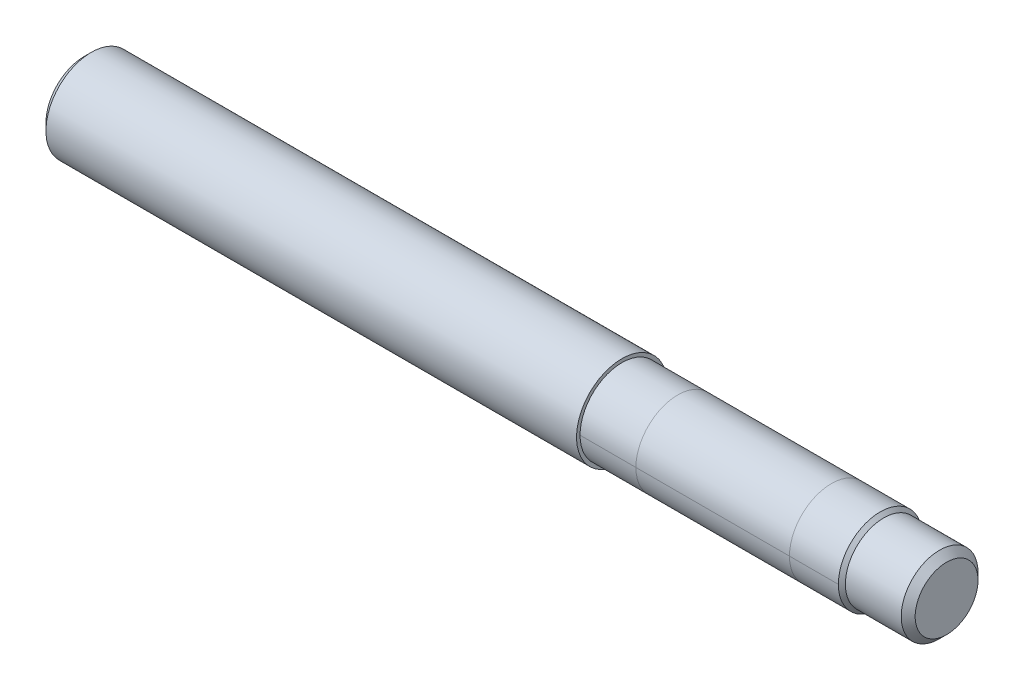
SolidWorks part; units mm, degrees
material "Alloy Steel"
ref_plane "Front" through (0, 0, 0) normal (0, 0, 1) x (1, 0, 0)
ref_plane "Top" through (0, 0, 0) normal (0, 1, 0) x (1, 0, 0)
ref_plane "Right" through (0, 0, 0) normal (1, 0, 0) x (0, 0, -1)
sketch "Sketch1" plane through (0, 0, 0) normal (1, 0, 0) x (0, 0, -1)
  circle A0 centre (0, 0) radius 6.5
  dimension "D1" = 13
extrude "Extrude1" add sketch "Sketch1" along normal blind 123.5
sketch "Sketch2" plane through (123.5, 0, 0) normal (1, 0, 0) x (0, 0, -1)
  circle A0 centre (0, 0) radius 6
  dimension "D1" = 12
extrude "Cut-Extrude1" cut sketch "Sketch2" against normal blind 46.5 flip side to cut
sketch "Sketch3" plane through (0, 0, 0) normal (0, 0, 1) x (1, 0, 0)
  line L0 (123.5, 10.254) -> (123.5, 5.5)
  line L1 (123.5, 5.5) -> (114.5, 5.5)
  line L2 (114.5, 5.5) -> (112.6001, 7.3999)
  line L3 (112.6001, 7.3999) -> (112.6001, 10.254)
  line L4 (112.6001, 10.254) -> (123.5, 10.254)
  line L5 (123.5, -6) -> (123.5, 6) construction
  line L6 (127.965, 0) -> (95.5626, 0) construction
  line L7 (77, 0) -> (0, 0) construction
  dimension "D1" = 11
  dimension "D2" = 9
  dimension "D3" = 45
revolve "Cut-Revolve1" cut sketch "Sketch3" angle 360 about L6
chamfer "Chamfer1" distance 1 angle 45 2 edges at (123.5, 0, -5.5) (0, 0, -6.5)
sketch "Sketch5" plane through (0, 0, 0) normal (0, 0, 1) x (1, 0, 0)
  line L0 (77, 0) -> (114, 0)
  line L1 (77, -6.5) -> (77, 6.5) construction
  line L2 (114, -6) -> (114, 6) construction
split line "Split Line1"
sketch "Sketch6" plane through (0, 0, 0) normal (0, 0, 1) x (1, 0, 0)
  line L0 (85.001, 6) -> (85.001, -6)
  line L1 (114, 6) -> (77, 6) construction
  line L2 (77, -6) -> (114, -6) construction
  line L3 (77, -6.5) -> (77, 6.5) construction
  dimension "D1" = 8.001
split line "Split Line2"
sketch "Sketch7" plane through (0, 0, 0) normal (0, 0, 1) x (1, 0, 0)
  line L0 (106.9974, 6) -> (106.9974, -6)
  line L3 (77, -6.5) -> (77, 6.5) construction
  dimension "D1" = 29.9974
split line "Split Line3"
